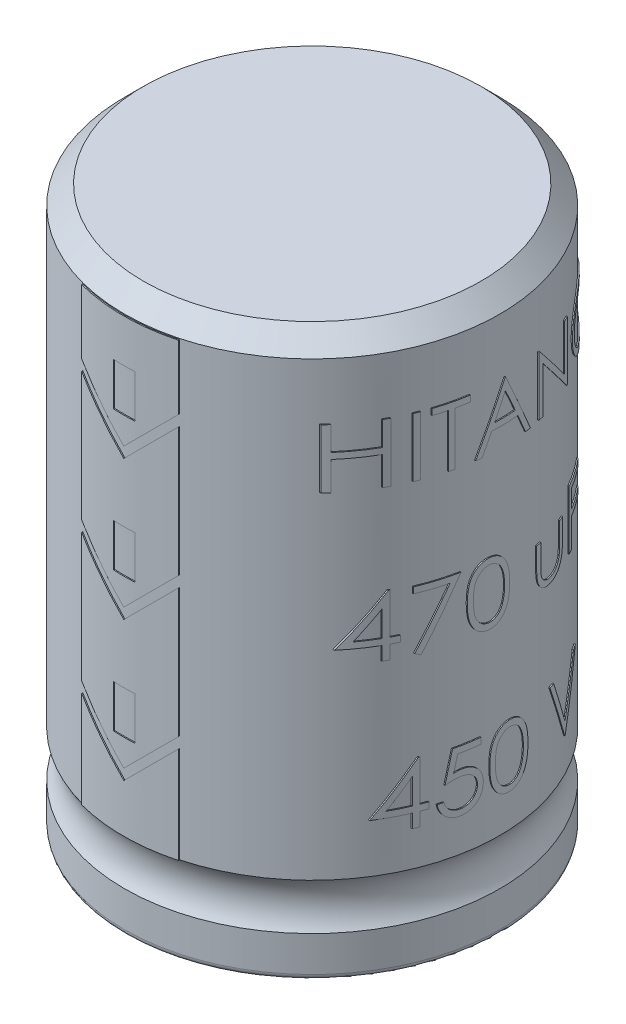
SolidWorks part; units mm, degrees
ref_plane "Front Plane" through (0, 0, 0) normal (0, 0, 1) x (1, 0, 0)
ref_plane "Top Plane" through (0, 0, 0) normal (0, 1, 0) x (1, 0, 0)
ref_plane "Right Plane" through (0, 0, 0) normal (1, 0, 0) x (0, 0, -1)
sketch "Sketch1" plane through (0, 0, 0) normal (1, 0, 0) x (0, 0, -1)
  line L0 (0, 32.893) -> (0, -40.2676) construction
  line L1 (0, 26.5253) -> (-15.7322, 26.5253)
  line L2 (-15.7322, 26.5253) -> (-17.5, 24.7575)
  line L3 (-17.5, 24.7575) -> (-17.5, -17.3247)
  line L4 (-17.5, -21.6247) -> (-17.5, -24.9276)
  line L5 (-16.9529, -25.4747) -> (0, -25.4747)
  line L6 (0, 26.5253) -> (0, -25.4747)
  arc A0 (-17.5, -17.3247) -> (-17.5, -21.6247) centre (-20.5589, -19.4747) cw
  arc A1 (-17.5, -24.9276) -> (-16.9529, -25.4747) centre (-16.9529, -24.9276) ccw
  dimension "D1" = 35
  dimension "D2" = 52
  dimension "D3" = 46
  dimension "D4" = 4.3
  dimension "D5" = 2.5
  dimension "D6" = 135
revolve "Revolve1" add sketch "Sketch1" angle 360 about L0
sketch "Sketch2" plane through (0, 0, 0) normal (0, 0, 1) x (1, 0, 0)
  line L0 (0, 31.0074) -> (0, -32.6533) construction
  line L1 (4.5374, 18.6707) -> (0.0374, 14.1707)
  line L2 (4.5374, 17.6707) -> (0.0374, 13.1707)
  line L3 (0.0374, 13.1707) -> (-4.4626, 17.6707)
  line L4 (0.0374, 14.1707) -> (-4.4626, 18.6707)
  line L5 (4.5374, 5.6707) -> (0.0374, 1.1707)
  line L6 (4.5374, 4.6707) -> (0.0374, 0.1707)
  line L7 (0.0374, 0.1707) -> (-4.4626, 4.6707)
  line L8 (0.0374, 1.1707) -> (-4.4626, 5.6707)
  line L9 (4.5374, -7.3293) -> (0.0374, -11.8293)
  line L10 (4.5374, -8.3293) -> (0.0374, -12.8293)
  line L11 (0.0374, -12.8293) -> (-4.4626, -8.3293)
  line L12 (0.0374, -11.8293) -> (-4.4626, -7.3293)
  line L14 (0.0374, 20.6707) -> (0.0374, -13.3293) construction
  line L15 (-4.4626, 24.6707) -> (-4.4626, 18.6707)
  line L16 (4.5374, 24.6707) -> (4.5374, 18.6707)
  line L17 (4.5374, 17.6707) -> (4.5374, 5.6707)
  line L18 (-4.4626, 17.6707) -> (-4.4626, 5.6707)
  line L19 (4.5374, 4.6707) -> (4.5374, -7.3293)
  line L20 (-4.4626, 4.6707) -> (-4.4626, -7.3293)
  line L21 (-4.4626, -8.3293) -> (-4.4626, -17.3263)
  line L22 (4.5374, -8.3293) -> (4.5374, -17.3263)
  line L23 (-4.4626, -17.3263) -> (4.5374, -17.3263)
  line L24 (-0.9626, 16.6707) -> (-0.9626, 20.6707)
  line L25 (-0.9626, 20.6707) -> (1.0374, 20.6707)
  line L26 (1.0374, 16.6707) -> (1.0374, 20.6707)
  line L27 (-0.9626, 16.6707) -> (1.0374, 16.6707)
  line L28 (-0.9626, 3.6707) -> (-0.9626, 7.6707)
  line L29 (-0.9626, 7.6707) -> (1.0374, 7.6707)
  line L30 (1.0374, 3.6707) -> (1.0374, 7.6707)
  line L31 (-0.9626, 3.6707) -> (1.0374, 3.6707)
  line L32 (-0.9626, -9.3293) -> (-0.9626, -5.3293)
  line L33 (-0.9626, -5.3293) -> (1.0374, -5.3293)
  line L34 (1.0374, -9.3293) -> (1.0374, -5.3293)
  line L35 (-0.9626, -9.3293) -> (1.0374, -9.3293)
  line L36 (4.5374, 24.6707) -> (-4.4626, 24.6707)
extrude "Boss-Extrude1" add sketch "Sketch2" along normal offset from surface (17.0051 mm away) 0.1
sketch "Sketch3" plane through (0, 0, 0) normal (1, 0, 0) x (0, 0, -1)
  line L0 (-12.7373, 14) -> (11.9589, 14) construction
  line L1 (-11.991, 0) -> (11.9589, 0) construction
  line L2 (-11.2447, -14) -> (11.9589, -14) construction
  text T0 "HITANO" font "Century Gothic" height 5.5
  text T1 "470 uF" font "Century Gothic" height 5.5
  text T2 "450 V" font "Century Gothic" height 5.5
  dimension "D1" = 14
  dimension "D2" = 14
extrude "Boss-Extrude2" add sketch "Sketch3" along normal offset from surface (13.2899 mm away) 0.1
sketch "Sketch4" plane through (0, -25.4747, 0) normal (0, -1, 0) x (1, 0, 0)
  line L0 (-0.7071, -7.9698) -> (-2.9698, -5.7071)
  line L1 (0.7071, 7.9698) -> (2.9698, 5.7071)
  line L2 (-0.7071, 7.9698) -> (-2.9698, 5.7071)
  line L3 (2.9698, 4.2929) -> (0.7071, 2.0302)
  line L4 (-2.9698, 4.2929) -> (-0.7071, 2.0302)
  line L5 (5.6321, 0) -> (-5.6321, 0) construction
  line L10 (-2.2627, 5) -> (2.2627, 5) construction
  line L11 (-2.9698, -4.2929) -> (-0.7071, -2.0302)
  line L12 (2.9698, -4.2929) -> (0.7071, -2.0302)
  line L13 (0.7071, -7.9698) -> (2.9698, -5.7071)
  arc A0 (2.9698, 5.7071) -> (2.9698, 4.2929) centre (2.2627, 5) cw
  arc A1 (0.7071, 2.0302) -> (-0.7071, 2.0302) centre (0, 2.7373) cw
  arc A2 (-2.9698, 5.7071) -> (-2.9698, 4.2929) centre (-2.2627, 5) ccw
  arc A3 (-0.7071, 7.9698) -> (0.7071, 7.9698) centre (0, 7.2627) cw
  arc A8 (-0.7071, -7.9698) -> (0.7071, -7.9698) centre (0, -7.2627) ccw
  arc A9 (-2.9698, -5.7071) -> (-2.9698, -4.2929) centre (-2.2627, -5) cw
  arc A10 (0.7071, -2.0302) -> (-0.7071, -2.0302) centre (0, -2.7373) ccw
  arc A11 (2.9698, -5.7071) -> (2.9698, -4.2929) centre (2.2627, -5) ccw
  dimension "D1" = 1
  dimension "D2" = 10
  dimension "D3" = 5.2
  dimension "D4" = 5.2
extrude "Boss-Extrude3" add sketch "Sketch4" along normal blind 0.1
sketch "Sketch5" plane through (0, -25.5747, 0) normal (0, -1, 0) x (1, 0, 0)
  line L0 (-0.5303, 5) -> (0, 4.4697)
  line L1 (-0.5303, 5) -> (0, 5.5303)
  line L2 (0, 4.4697) -> (0.5303, 5)
  line L3 (0, 5.5303) -> (0.5303, 5)
  line L4 (0, -4.913) -> (0, 4.251) construction
  line L5 (-2.2448, 0) -> (3.7623, 0) construction
  line L6 (-3.2627, 5) -> (3.2627, 5) construction
  line L7 (0, -4.4697) -> (0.5303, -5)
  line L8 (0, -5.5303) -> (0.5303, -5)
  line L9 (-0.5303, -5) -> (0, -5.5303)
  line L10 (-0.5303, -5) -> (0, -4.4697)
  arc A1 (-2.9698, 5.7071) -> (-2.9698, 4.2929) centre (-2.2627, 5) ccw construction
  arc A2 (2.9698, 4.2929) -> (2.9698, 5.7071) centre (2.2627, 5) ccw construction
  dimension "D1" = 0.75
  dimension "D2" = 0.75
extrude "Boss-Extrude4" add sketch "Sketch5" along normal blind 6
